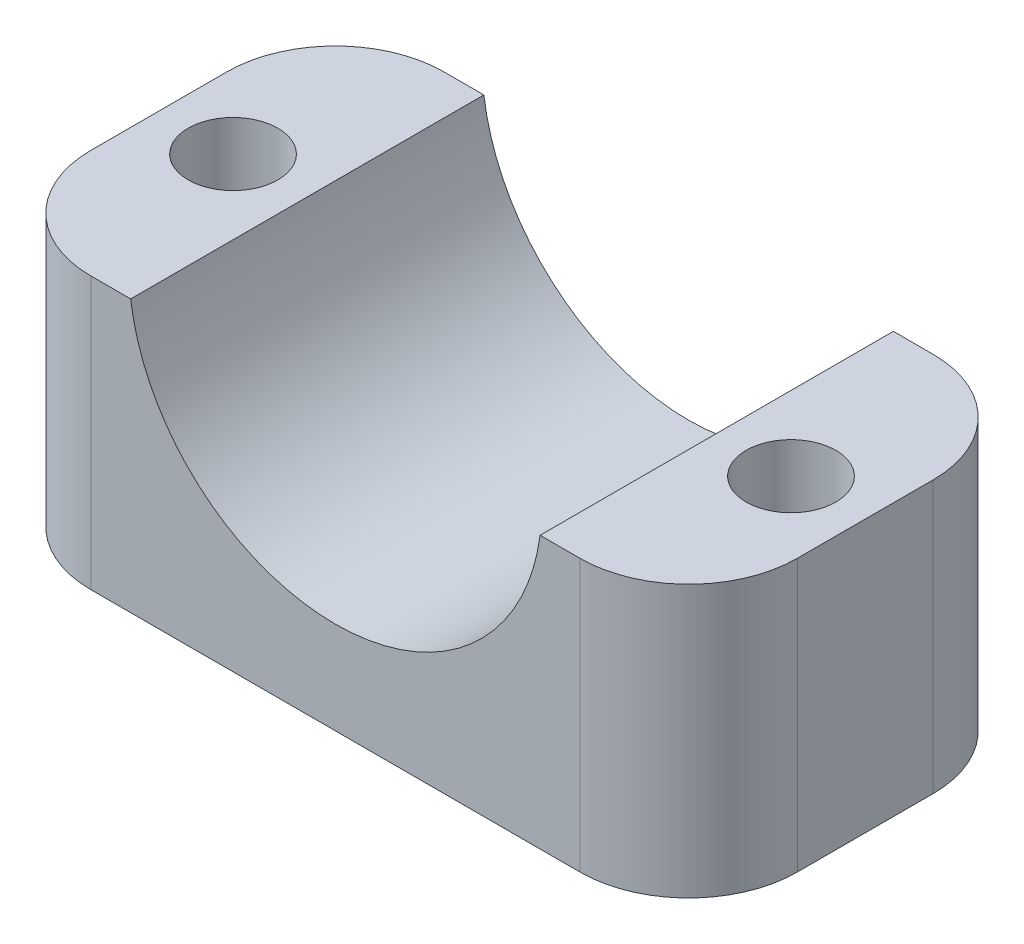
SolidWorks part; units mm, degrees
ref_plane "Front Plane" through (0, 0, 0) normal (0, 0, 1) x (1, 0, 0)
ref_plane "Top Plane" through (0, 0, 0) normal (0, 1, 0) x (1, 0, 0)
ref_plane "Right Plane" through (0, 0, 0) normal (1, 0, 0) x (0, 0, -1)
sketch "Sketch1" plane through (0, 0, 0) normal (0, 0, 1) x (1, 0, 0)
  line L1 (-13, -5) -> (13, -5)
  line L2 (-13, -5) -> (-13, 5)
  line L3 (-13, 5) -> (13, 5)
  line L4 (13, -5) -> (13, 5)
  line L5 (-13, -5) -> (13, 5) construction
  line L6 (-13, 5) -> (13, -5) construction
  point P0 (0, 0)
  dimension "D1" = 26
  dimension "D2" = 10
extrude "Boss-Extrude1" add sketch "Sketch1" along normal blind 13
sketch "Sketch2" plane through (0, 0, 13) normal (0, 0, 1) x (1, 0, 0)
  line L0 (0, 0) -> (0, 6) construction
  line L1 (13, 5) -> (-13, 5) construction
  circle A0 centre (0, 6) radius 7.6
  dimension "D1" = 15.2
  dimension "D2" = 1
extrude "Cut-Extrude1" cut sketch "Sketch2" against normal through all
sketch "Sketch3" plane through (0, 5, 0) normal (0, 1, 0) x (1, 0, 0)
  line L0 (13, 0) -> (7.5339, -13) construction
  line L1 (-13, 0) -> (-7.5339, -13) construction
  circle A0 centre (-10.267, -6.5) radius 1.65
  circle A1 centre (10.267, -6.5) radius 1.65
  dimension "D1" = 3.3
extrude "Cut-Extrude2" cut sketch "Sketch3" against normal blind 10
fillet "Fillet2" radius 4 4 edges at (-13, 0, 13) (13, 0, 0) (13, 0, 13) (-13, 0, 0)
